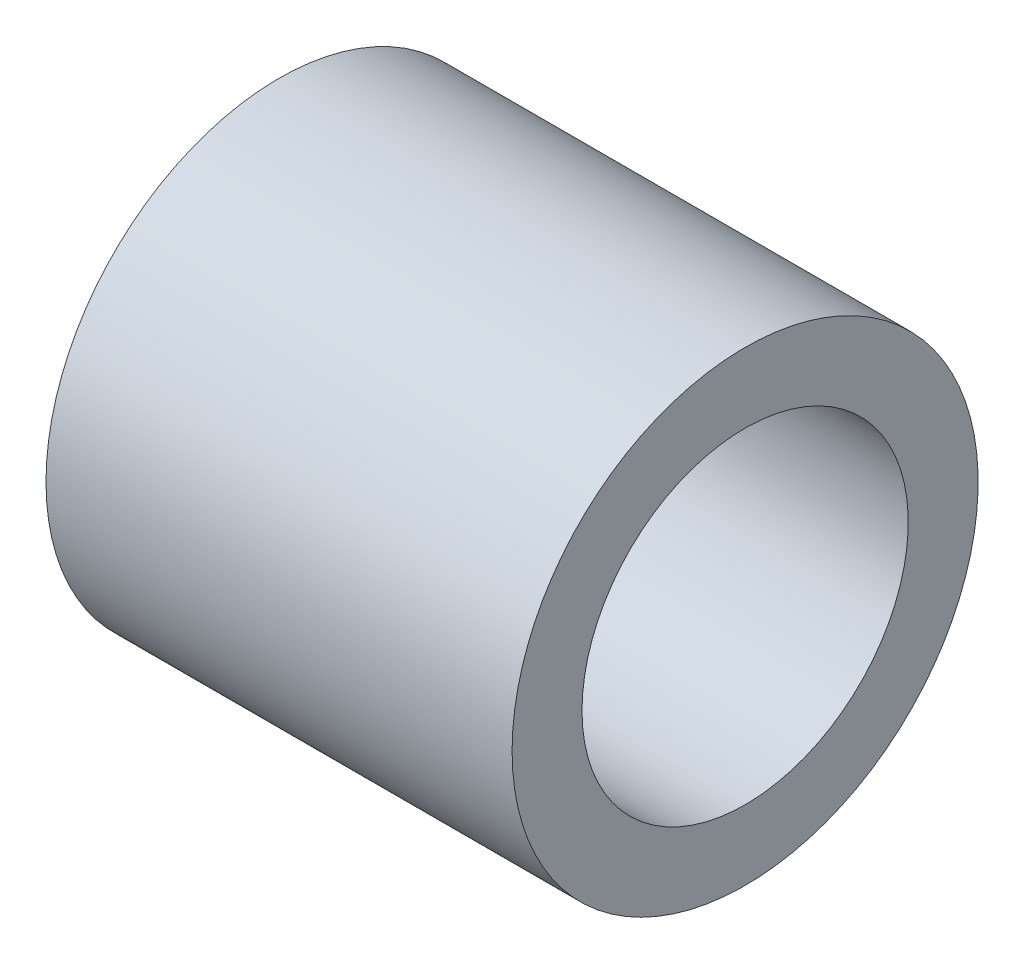
SolidWorks part; units mm, degrees
ref_plane "face" through (0, 0, 0) normal (0, 0, 1) x (1, 0, 0)
ref_plane "dessus" through (0, 0, 0) normal (0, 1, 0) x (1, 0, 0)
ref_plane "droite" through (0, 0, 0) normal (1, 0, 0) x (0, 0, -1)
sketch "Esquisse1" plane through (0, 0, 0) normal (0, 0, 1) x (1, 0, 0)
  line L0 (0, 0) -> (30, 0) construction
  line L2 (0, 7) -> (20, 7)
  line L3 (0, 7) -> (0, 10)
  line L4 (0, 10) -> (20, 10)
  line L5 (20, 7) -> (20, 10)
  dimension "D1" = 7
  dimension "D2" = 10
  dimension "D3" = 20
revolve "Base-Révolution" add sketch "Esquisse1" angle 360 about L0
ref_plane "Plan1" through (10, 0, 0) normal (1, 0, 0) x (0, 0, -1)
